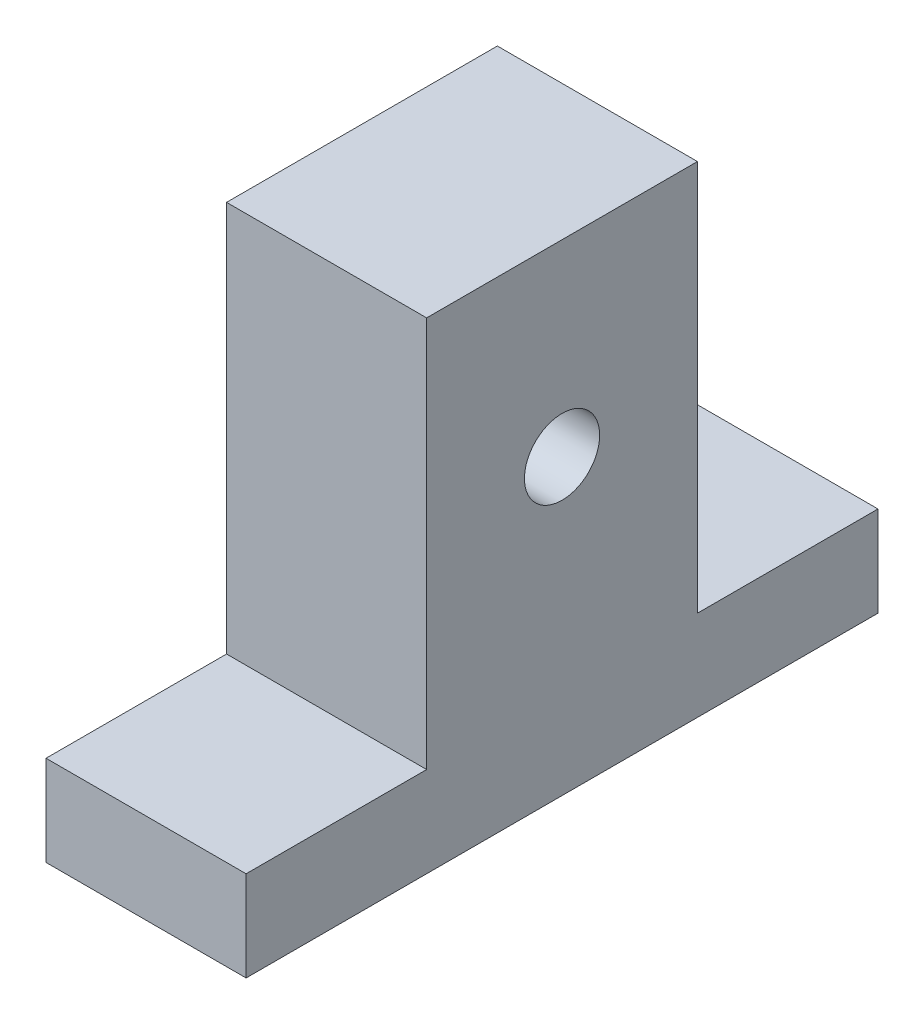
SolidWorks part; units mm, degrees
material "A286 铁基超合金"
ref_plane "前视基准面" through (0, 0, 0) normal (0, 0, 1) x (1, 0, 0)
ref_plane "上视基准面" through (0, 0, 0) normal (0, 1, 0) x (1, 0, 0)
ref_plane "右视基准面" through (0, 0, 0) normal (1, 0, 0) x (0, 0, -1)
other "Configuration Table"
sketch "草图1" plane through (0, 0, 0) normal (1, 0, 0) x (0, 0, -1)
  line L0 (-73.8395, -90.4346) -> (-31.8395, -90.4346)
  line L1 (-31.8395, -90.4346) -> (-31.8395, -84.4346)
  line L2 (-31.8395, -84.4346) -> (-43.8395, -84.4346)
  line L3 (-43.8395, -84.4346) -> (-43.8395, -58.4346)
  line L4 (-43.8395, -58.4346) -> (-61.8395, -58.4346)
  line L5 (-61.8395, -58.4346) -> (-61.8395, -84.4346)
  line L6 (-61.8395, -84.4346) -> (-73.8395, -84.4346)
  line L7 (-73.8395, -84.4346) -> (-73.8395, -90.4346)
  line L8 (-52.8395, -58.4346) -> (-52.8395, -70.9346) construction
  circle A0 centre (-52.8395, -70.9346) radius 2.5
  dimension "D6" = 5
  dimension "D1" = 42
  dimension "D2" = 12
  dimension "D3" = 12
  dimension "D4" = 26
  dimension "D5" = 12.5
  dimension "D7" = 6
  dimension "D8" = 6
extrude "凸台-拉伸1" add sketch "草图1" along normal blind 13.3
